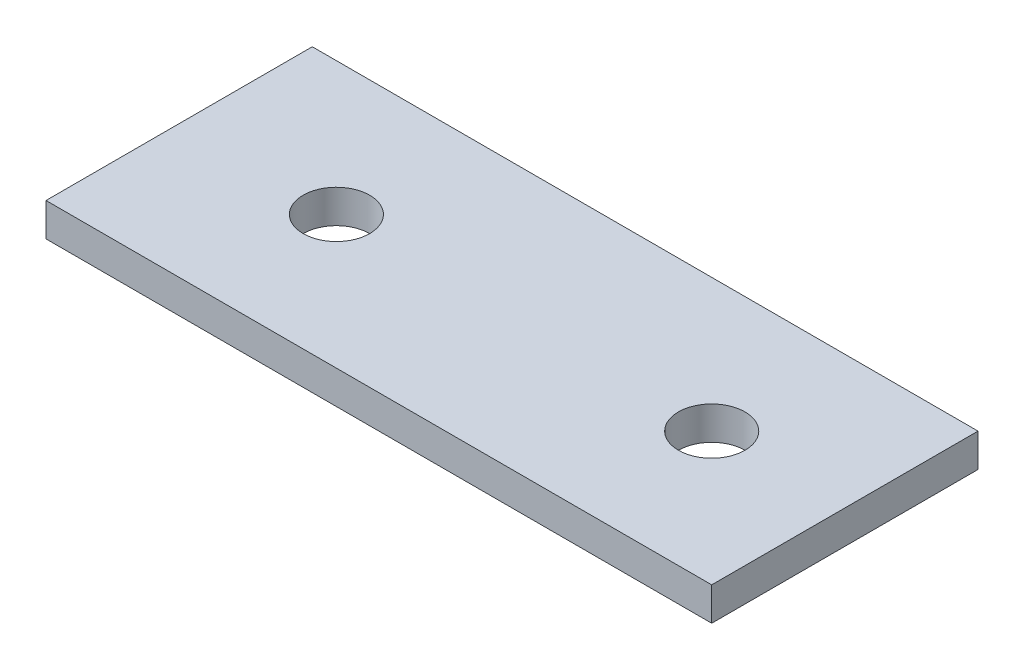
SolidWorks part; units mm, degrees
ref_plane "Front Plane" through (0, 0, 0) normal (0, 0, 1) x (1, 0, 0)
ref_plane "Top Plane" through (0, 0, 0) normal (0, 1, 0) x (1, 0, 0)
ref_plane "Right Plane" through (0, 0, 0) normal (1, 0, 0) x (0, 0, -1)
sketch "Sketch1" plane through (0, 0, 0) normal (0, 1, 0) x (1, 0, 0)
  line L1 (-31.75, 12.7) -> (31.75, 12.7)
  line L2 (-31.75, 12.7) -> (-31.75, -12.7)
  line L3 (-31.75, -12.7) -> (31.75, -12.7)
  line L4 (31.75, 12.7) -> (31.75, -12.7)
  line L5 (-31.75, 12.7) -> (31.75, -12.7) construction
  line L6 (-31.75, -12.7) -> (31.75, 12.7) construction
  point P0 (0, 0)
  dimension "D1" = 63.5
  dimension "D2" = 25.4
extrude "Boss-Extrude1" add sketch "Sketch1" along normal blind 3.175
sketch "Sketch2" plane through (0, 3.175, 0) normal (0, 1, 0) x (1, 0, 0)
  line L0 (-31.75, -12.7) -> (31.75, -12.7) construction
  line L1 (-31.75, 12.7) -> (-31.75, -12.7) construction
  circle A0 centre (-16.75, 0) radius 3.175
  circle A1 centre (19.05, 0) radius 3.175
  dimension "D1" = 12.7
  dimension "D2" = 12.7
  dimension "D3" = 15
  dimension "D4" = 50.8
  dimension "D5" = 6.35
extrude "Cut-Extrude1" cut sketch "Sketch2" against normal up to next
